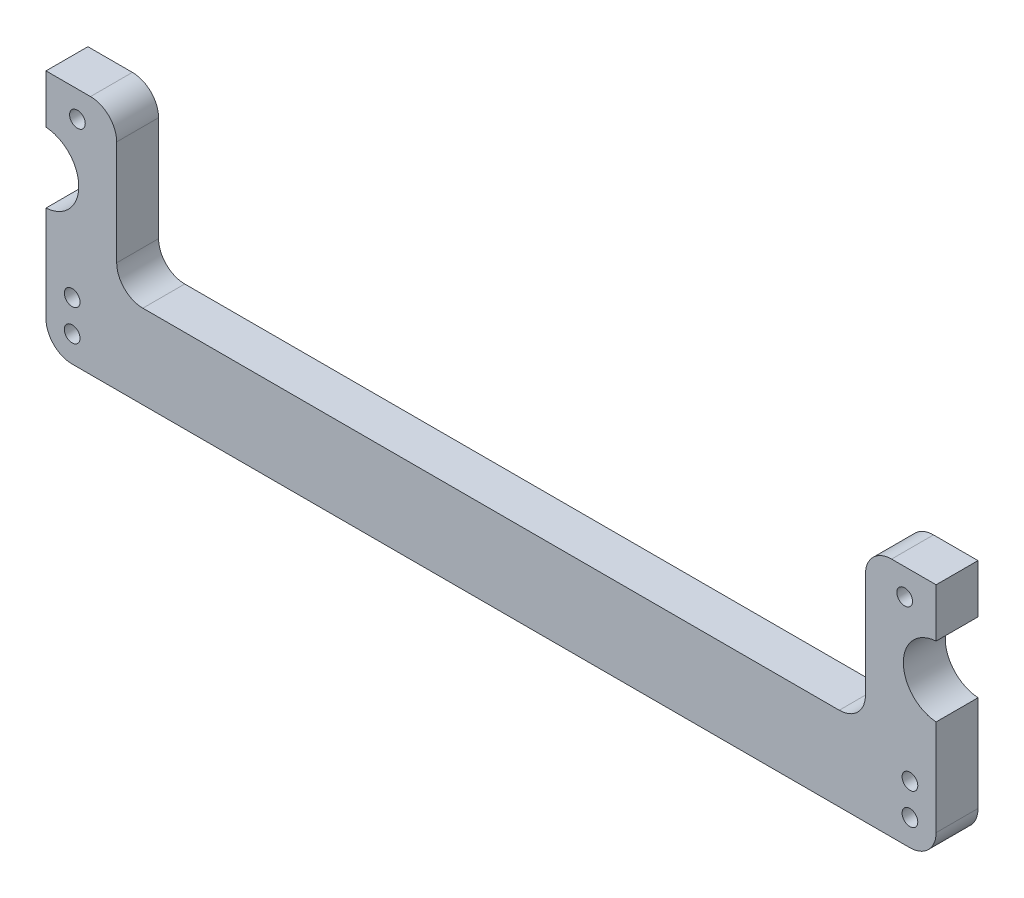
SolidWorks part; units mm, degrees
ref_plane "前视基准面" through (0, 0, 0) normal (0, 0, 1) x (1, 0, 0)
ref_plane "上视基准面" through (0, 0, 0) normal (0, 1, 0) x (1, 0, 0)
ref_plane "右视基准面" through (0, 0, 0) normal (1, 0, 0) x (0, 0, -1)
sketch "草图1" plane through (0, 0, 0) normal (0, 0, 1) x (1, 0, 0)
  line L0 (0, 8) -> (170, 8) construction
  line L1 (5, 0) -> (165, 0)
  line L2 (0, 5) -> (0, 11)
  line L3 (18.5, 16) -> (151.5, 16)
  line L4 (170, 5) -> (170, 11)
  line L5 (85, 16) -> (85, 0) construction
  line L6 (0, 16) -> (0, 11)
  line L7 (161.5, 46) -> (170, 46)
  line L8 (13.5, 21) -> (13.5, 41)
  line L9 (8.5, 46) -> (0, 46)
  line L10 (0, 16) -> (0, 46)
  line L11 (156.5, 21) -> (156.5, 41)
  line L12 (170, 16) -> (170, 46)
  line L13 (170, 16) -> (170, 11)
  circle A0 centre (5, 11) radius 1.5
  circle A1 centre (5, 5) radius 1.5
  circle A2 centre (165, 5) radius 1.5
  circle A3 centre (165, 11) radius 1.5
  arc A4 (165, 0) -> (170, 5) centre (165, 5) ccw
  arc A5 (156.5, 21) -> (151.5, 16) centre (151.5, 21) cw
  arc A6 (5, 0) -> (0, 5) centre (5, 5) cw
  arc A7 (18.5, 16) -> (13.5, 21) centre (18.5, 21) cw
  arc A8 (161.5, 46) -> (156.5, 41) centre (161.5, 41) ccw
  arc A9 (13.5, 41) -> (8.5, 46) centre (8.5, 41) ccw
  circle A10 centre (6, 41) radius 1.5
  circle A11 centre (164, 41) radius 1.5
  point P19 (170, 0)
  point P24 (0, 0)
  point P27 (0, 16)
  point P34 (156.5, 16)
  point P37 (13.5, 16)
  point P40 (156.5, 46)
  point P43 (13.5, 46)
  dimension "D3" = 3
  dimension "D6" = 5
  dimension "D10" = 5
  dimension "D11" = 5
  dimension "D13" = 3
  dimension "D1" = 170
  dimension "D2" = 16
  dimension "D4" = 5
  dimension "D5" = 5
  dimension "D7" = 143
  dimension "D8" = 30
  dimension "D9" = 30
  dimension "D12" = 6
  dimension "D14" = 25
extrude "凸台-拉伸1" add sketch "草图1" along normal blind 8
sketch "草图2" plane through (0, 0, 8) normal (0, 0, 1) x (1, 0, 0)
  line L0 (-0.44, 36.7) -> (-0.44, 23.3)
  line L1 (170.44, 36.7) -> (170.44, 23.3)
  arc A3 (170.44, 36.7) -> (170.44, 23.3) centre (170.44, 30) ccw
  arc A4 (170.44, 36.7) -> (170.44, 23.3) centre (170.44, 30) ccw
  arc A6 (-0.44, 23.3) -> (-0.44, 36.7) centre (-0.44, 30) ccw
  arc A7 (-0.44, 23.3) -> (-0.44, 36.7) centre (-0.44, 30) ccw
  dimension "D1" = 1
  dimension "D2" = 1
extrude "切除-拉伸1" cut sketch "草图2" against normal through all
